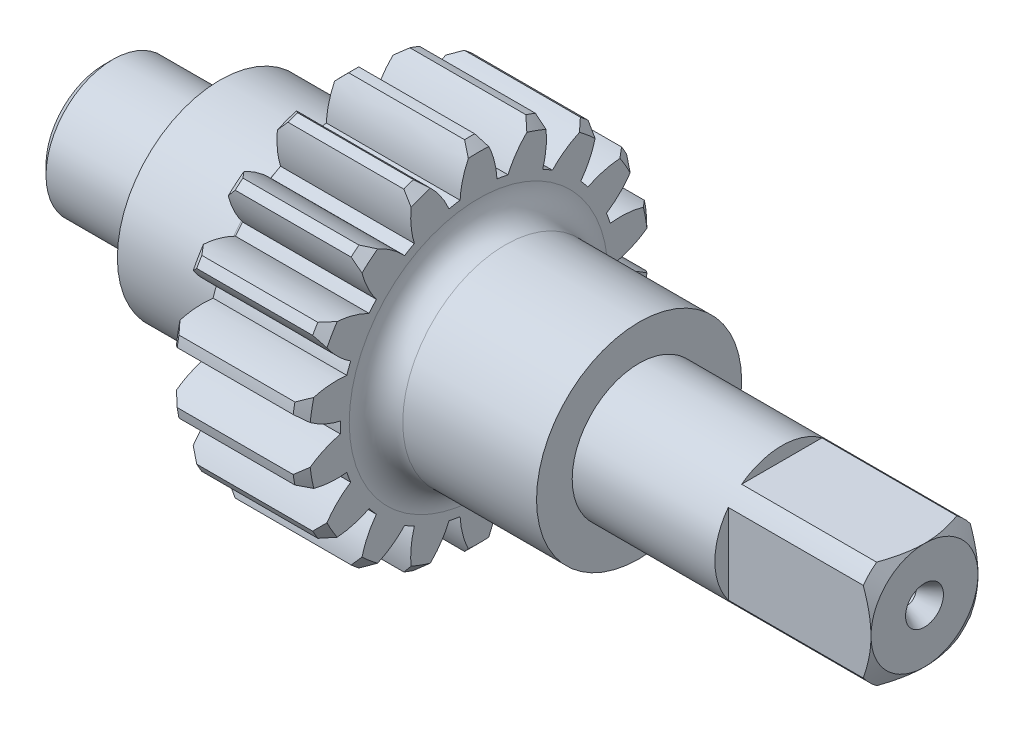
SolidWorks part; units mm, degrees
ref_plane "Front Plane" through (0, 0, 0) normal (0, 0, 1) x (1, 0, 0)
ref_plane "Top Plane" through (0, 0, 0) normal (0, 1, 0) x (1, 0, 0)
ref_plane "Right Plane" through (0, 0, 0) normal (1, 0, 0) x (0, 0, -1)
sketch "Sketch2" plane through (0, 0, 0) normal (0, 0, 1) x (1, 0, 0)
  line L0 (0, 0) -> (92, 0)
  line L1 (92, 0) -> (92, 7.5)
  line L2 (92, 7.5) -> (60, 7.5)
  line L3 (60, 7.5) -> (60, 11.5)
  line L4 (60, 11.5) -> (45, 11.5)
  line L5 (42, 14.5) -> (42, 15.5)
  line L6 (42, 15.5) -> (27, 15.5)
  line L7 (27, 15.5) -> (27, 14.5)
  line L8 (24, 11.5) -> (13, 11.5)
  line L9 (13, 11.5) -> (13, 7.5)
  line L10 (13, 7.5) -> (0, 7.5)
  line L11 (0, 7.5) -> (0, 0)
  arc A0 (45, 11.5) -> (42, 14.5) centre (45, 14.5) cw
  arc A1 (27, 14.5) -> (24, 11.5) centre (24, 14.5) cw
  point P17 (27, 11.5)
  dimension "D9" = 3
  dimension "D1" = 13
  dimension "D2" = 14
  dimension "D3" = 47
  dimension "D4" = 15
  dimension "D5" = 92
  dimension "D6" = 7.5
  dimension "D7" = 11.5
  dimension "D8" = 15.5
revolve "Revolve1" add sketch "Sketch2" angle 360 about L0
sketch "Sketch3" plane through (42, 0, 0) normal (1, 0, 0) x (0, 0, -1)
  line L0 (0, 15.5) -> (0, 0) construction
  circle A0 centre (0, 0) radius 15.5 construction
  arc A1 (0.57, 19.9919) -> (-0.57, 19.9919) centre (0, 0) ccw
  circle A2 centre (0, 0) radius 18 construction
  arc A3 (2.07, 15.3612) -> (-2.07, 15.3612) centre (0, 0) ccw
  arc A4 (7.199, 13.7268) -> (3.3087, 15.1427) centre (0, 0) ccw
  arc A5 (7.3732, 18.5913) -> (6.302, 18.9812) centre (0, 0) ccw
  arc A6 (11.4597, 10.4368) -> (8.2882, 13.0979) centre (0, 0) ccw
  arc A7 (13.2872, 14.9483) -> (12.4139, 15.6811) centre (0, 0) ccw
  arc A8 (14.3382, 5.8879) -> (12.2682, 9.4733) centre (0, 0) ccw
  arc A9 (17.5985, 9.5023) -> (17.0285, 10.4896) centre (0, 0) ccw
  arc A10 (15.4872, 0.6289) -> (14.7683, 4.706) centre (0, 0) ccw
  arc A11 (19.7871, 2.9102) -> (19.5892, 4.0329) centre (0, 0) ccw
  arc A12 (14.7683, -4.706) -> (15.4872, -0.6289) centre (0, 0) ccw
  arc A13 (19.5892, -4.0329) -> (19.7871, -2.9102) centre (0, 0) ccw
  arc A14 (12.2682, -9.4733) -> (14.3382, -5.8879) centre (0, 0) ccw
  arc A15 (17.0285, -10.4896) -> (17.5985, -9.5023) centre (0, 0) ccw
  arc A16 (8.2882, -13.0979) -> (11.4597, -10.4368) centre (0, 0) ccw
  arc A17 (12.4139, -15.6811) -> (13.2872, -14.9483) centre (0, 0) ccw
  arc A18 (3.3087, -15.1427) -> (7.199, -13.7268) centre (0, 0) ccw
  arc A19 (6.302, -18.9812) -> (7.3732, -18.5913) centre (0, 0) ccw
  arc A20 (-2.07, -15.3612) -> (2.07, -15.3612) centre (0, 0) ccw
  arc A21 (-0.57, -19.9919) -> (0.57, -19.9919) centre (0, 0) ccw
  arc A22 (-7.199, -13.7268) -> (-3.3087, -15.1427) centre (0, 0) ccw
  arc A23 (-7.3732, -18.5913) -> (-6.302, -18.9812) centre (0, 0) ccw
  arc A24 (-11.4597, -10.4368) -> (-8.2882, -13.0979) centre (0, 0) ccw
  arc A25 (-13.2872, -14.9483) -> (-12.4139, -15.6811) centre (0, 0) ccw
  arc A26 (-14.3382, -5.8879) -> (-12.2682, -9.4733) centre (0, 0) ccw
  arc A27 (-17.5985, -9.5023) -> (-17.0285, -10.4896) centre (0, 0) ccw
  arc A28 (-15.4872, -0.6289) -> (-14.7683, -4.706) centre (0, 0) ccw
  arc A29 (-19.7871, -2.9102) -> (-19.5892, -4.0329) centre (0, 0) ccw
  arc A30 (-14.7683, 4.706) -> (-15.4872, 0.6289) centre (0, 0) ccw
  arc A31 (-19.5892, 4.0329) -> (-19.7871, 2.9102) centre (0, 0) ccw
  arc A32 (-12.2682, 9.4733) -> (-14.3382, 5.8879) centre (0, 0) ccw
  arc A33 (-17.0285, 10.4896) -> (-17.5985, 9.5023) centre (0, 0) ccw
  arc A34 (-8.2882, 13.0979) -> (-11.4597, 10.4368) centre (0, 0) ccw
  arc A35 (-12.4139, 15.6811) -> (-13.2872, 14.9483) centre (0, 0) ccw
  arc A36 (-3.3087, 15.1427) -> (-7.199, 13.7268) centre (0, 0) ccw
  arc A37 (-6.302, 18.9812) -> (-7.3732, 18.5913) centre (0, 0) ccw
  spline S0 degree 2 poles (-0.57, 19.9919) (-1.923, 17.8777) (-2.07, 15.3612) knots 0 0 0 1 1 1
  spline S1 degree 2 poles (0.57, 19.9919) (1.923, 17.8777) (2.07, 15.3612) knots 0 0 0 1 1 1
  spline S2 degree 2 poles (6.302, 18.9812) (4.3075, 17.4572) (3.3087, 15.1427) knots 0 0 0 1 1 1
  spline S3 degree 2 poles (7.3732, 18.5913) (7.9215, 16.1418) (7.199, 13.7268) knots 0 0 0 1 1 1
  spline S4 degree 2 poles (12.4139, 15.6811) (10.0185, 14.9311) (8.2882, 13.0979) knots 0 0 0 1 1 1
  spline S5 degree 2 poles (13.2872, 14.9483) (12.9646, 12.459) (11.4597, 10.4368) knots 0 0 0 1 1 1
  spline S6 degree 2 poles (17.0285, 10.4896) (14.521, 10.6042) (12.2682, 9.4733) knots 0 0 0 1 1 1
  spline S7 degree 2 poles (17.5985, 9.5023) (16.444, 7.2735) (14.3382, 5.8879) knots 0 0 0 1 1 1
  spline S8 degree 2 poles (19.5892, 4.0329) (17.2721, 4.9982) (14.7683, 4.706) knots 0 0 0 1 1 1
  spline S9 degree 2 poles (19.7871, 2.9102) (17.94, 1.2107) (15.4872, 0.6289) knots 0 0 0 1 1 1
  spline S10 degree 2 poles (19.7871, -2.9102) (17.94, -1.2107) (15.4872, -0.6289) knots 0 0 0 1 1 1
  spline S11 degree 2 poles (19.5892, -4.0329) (17.2721, -4.9982) (14.7683, -4.706) knots 0 0 0 1 1 1
  spline S12 degree 2 poles (17.5985, -9.5023) (16.444, -7.2735) (14.3382, -5.8879) knots 0 0 0 1 1 1
  spline S13 degree 2 poles (17.0285, -10.4896) (14.521, -10.6042) (12.2682, -9.4733) knots 0 0 0 1 1 1
  spline S14 degree 2 poles (13.2872, -14.9483) (12.9646, -12.459) (11.4597, -10.4368) knots 0 0 0 1 1 1
  spline S15 degree 2 poles (12.4139, -15.6811) (10.0185, -14.9311) (8.2882, -13.0979) knots 0 0 0 1 1 1
  spline S16 degree 2 poles (7.3732, -18.5913) (7.9215, -16.1418) (7.199, -13.7268) knots 0 0 0 1 1 1
  spline S17 degree 2 poles (6.302, -18.9812) (4.3075, -17.4572) (3.3087, -15.1427) knots 0 0 0 1 1 1
  spline S18 degree 2 poles (0.57, -19.9919) (1.923, -17.8777) (2.07, -15.3612) knots 0 0 0 1 1 1
  spline S19 degree 2 poles (-0.57, -19.9919) (-1.923, -17.8777) (-2.07, -15.3612) knots 0 0 0 1 1 1
  spline S20 degree 2 poles (-6.302, -18.9812) (-4.3075, -17.4572) (-3.3087, -15.1427) knots 0 0 0 1 1 1
  spline S21 degree 2 poles (-7.3732, -18.5913) (-7.9215, -16.1418) (-7.199, -13.7268) knots 0 0 0 1 1 1
  spline S22 degree 2 poles (-12.4139, -15.6811) (-10.0185, -14.9311) (-8.2882, -13.0979) knots 0 0 0 1 1 1
  spline S23 degree 2 poles (-13.2872, -14.9483) (-12.9646, -12.459) (-11.4597, -10.4368) knots 0 0 0 1 1 1
  spline S24 degree 2 poles (-17.0285, -10.4896) (-14.521, -10.6042) (-12.2682, -9.4733) knots 0 0 0 1 1 1
  spline S25 degree 2 poles (-17.5985, -9.5023) (-16.444, -7.2735) (-14.3382, -5.8879) knots 0 0 0 1 1 1
  spline S26 degree 2 poles (-19.5892, -4.0329) (-17.2721, -4.9982) (-14.7683, -4.706) knots 0 0 0 1 1 1
  spline S27 degree 2 poles (-19.7871, -2.9102) (-17.94, -1.2107) (-15.4872, -0.6289) knots 0 0 0 1 1 1
  spline S28 degree 2 poles (-19.7871, 2.9102) (-17.94, 1.2107) (-15.4872, 0.6289) knots 0 0 0 1 1 1
  spline S29 degree 2 poles (-19.5892, 4.0329) (-17.2721, 4.9982) (-14.7683, 4.706) knots 0 0 0 1 1 1
  spline S30 degree 2 poles (-17.5985, 9.5023) (-16.444, 7.2735) (-14.3382, 5.8879) knots 0 0 0 1 1 1
  spline S31 degree 2 poles (-17.0285, 10.4896) (-14.521, 10.6042) (-12.2682, 9.4733) knots 0 0 0 1 1 1
  spline S32 degree 2 poles (-13.2872, 14.9483) (-12.9646, 12.459) (-11.4597, 10.4368) knots 0 0 0 1 1 1
  spline S33 degree 2 poles (-12.4139, 15.6811) (-10.0185, 14.9311) (-8.2882, 13.0979) knots 0 0 0 1 1 1
  spline S34 degree 2 poles (-7.3732, 18.5913) (-7.9215, 16.1418) (-7.199, 13.7268) knots 0 0 0 1 1 1
  spline S35 degree 2 poles (-6.302, 18.9812) (-4.3075, 17.4572) (-3.3087, 15.1427) knots 0 0 0 1 1 1
  point P117 (0, 0)
  dimension "D1" = 40
  dimension "D2" = 36
  dimension "D3" = 0.5
  dimension "D4" = 2.07
  dimension "D5" = 0.57
  dimension "D6" = 18
extrude "Boss-Extrude1" add sketch "Sketch3" against normal up to surface (15 mm away) up to face at (27, 0, 14.5)
sketch "Sketch4" plane through (0, 0, 0) normal (0, 1, 0) x (1, 0, 0)
  line L0 (92, 0) -> (72.0944, 0) construction
  line L1 (92, -7.5) -> (92, 7.5) construction
  line L2 (86.75, 0) -> (92, 0)
  line L3 (92, 0) -> (92, 2.1258)
  line L4 (92, 2.1258) -> (90.05, 1)
  line L5 (90.05, 1) -> (88.25, 1)
  line L6 (88.25, 1) -> (86.75, 0)
  line L7 (46, 28.1172) -> (46, -32.4349) construction
  line L8 (0, 7.5) -> (0, -7.5) construction
  line L9 (5.25, 0) -> (0, 0)
  line L10 (0, 0) -> (0, 2.1258)
  line L11 (0, 2.1258) -> (1.95, 1)
  line L12 (1.95, 1) -> (3.75, 1)
  line L13 (3.75, 1) -> (5.25, 0)
  dimension "D1" = 30
  dimension "D2" = 1
  dimension "D3" = 3.3
  dimension "D4" = 1.8
  dimension "D5" = 1.95
  dimension "D6" = 46
revolve "Cut-Revolve1" cut sketch "Sketch4" angle 360 about L0
chamfer "Chamfer1" distance 1 angle 45 1 edges at (0, 0, 7.5)
chamfer "Chamfer2" distance 1.5 angle 30 1 edges at (92, 0, 7.5)
sketch "Sketch7" plane through (92, 0, 0) normal (1, 0, 0) x (0, 0, -1)
  line L0 (-6, 6) -> (0, 11)
  line L1 (-6, 6) -> (6, 6)
  line L2 (-6, 6) -> (-6, -6)
  line L3 (-6, -6) -> (6, -6)
  line L4 (6, 6) -> (6, -6)
  line L5 (-6, 6) -> (6, -6) construction
  line L6 (-6, -6) -> (6, 6) construction
  line L7 (0, 11) -> (6, 6)
  line L8 (11, 0) -> (6, -6)
  line L9 (6, 6) -> (11, 0)
  line L10 (0, -11) -> (-6, -6)
  line L11 (6, -6) -> (0, -11)
  line L12 (-11, 0) -> (-6, 6)
  line L13 (-6, -6) -> (-11, 0)
  circle A0 centre (0, 0) radius 6 construction
  circle A1 centre (0, 0) radius 6
  point P20 (0, 0)
  dimension "D1" = 5
  dimension "D2" = 4
extrude "Cut-Extrude2" cut sketch "Sketch7" against normal blind 16 contours L7 L0 L1 | L9 L4 L8 | L13 L2 L12 | L11 L3 L10
chamfer "Chamfer3" distance 1 angle 45 18 edges at (42, -18.7939, -6.8404) (42, -15.3209, -12.8558) (42, -10, -17.3205) (42, -3.473, -19.6962) (42, 3.473, -19.6962) (42, 10, -17.3205) (42, 15.3209, -12.8558) (42, 18.7939, -6.8404) (42, 20, 0) (42, 18.7939, 6.8404) (42, 15.3209, 12.8558) (42, 10, 17.3205) (42, 3.473, 19.6962) (42, -3.473, 19.6962) (42, -10, 17.3205) (42, -20, 0) (42, -18.7939, 6.8404) (42, -15.3209, 12.8558)
chamfer "Chamfer4" distance 1 angle 45 18 edges at (27, -18.7939, -6.8404) (27, -20, 0) (27, -18.7939, 6.8404) (27, -15.3209, 12.8558) (27, -10, 17.3205) (27, -3.473, 19.6962) (27, 3.473, 19.6962) (27, 10, 17.3205) (27, 15.3209, 12.8558) (27, 18.7939, 6.8404) (27, 20, 0) (27, 18.7939, -6.8404) (27, 15.3209, -12.8558) (27, 10, -17.3205) (27, 3.473, -19.6962) (27, -15.3209, -12.8558) (27, -3.473, -19.6962) (27, -10, -17.3205)
scale "Scale1" scale about centroid uniform scaling yes scale factor 1.19
scale "Scale2" [suppressed]
